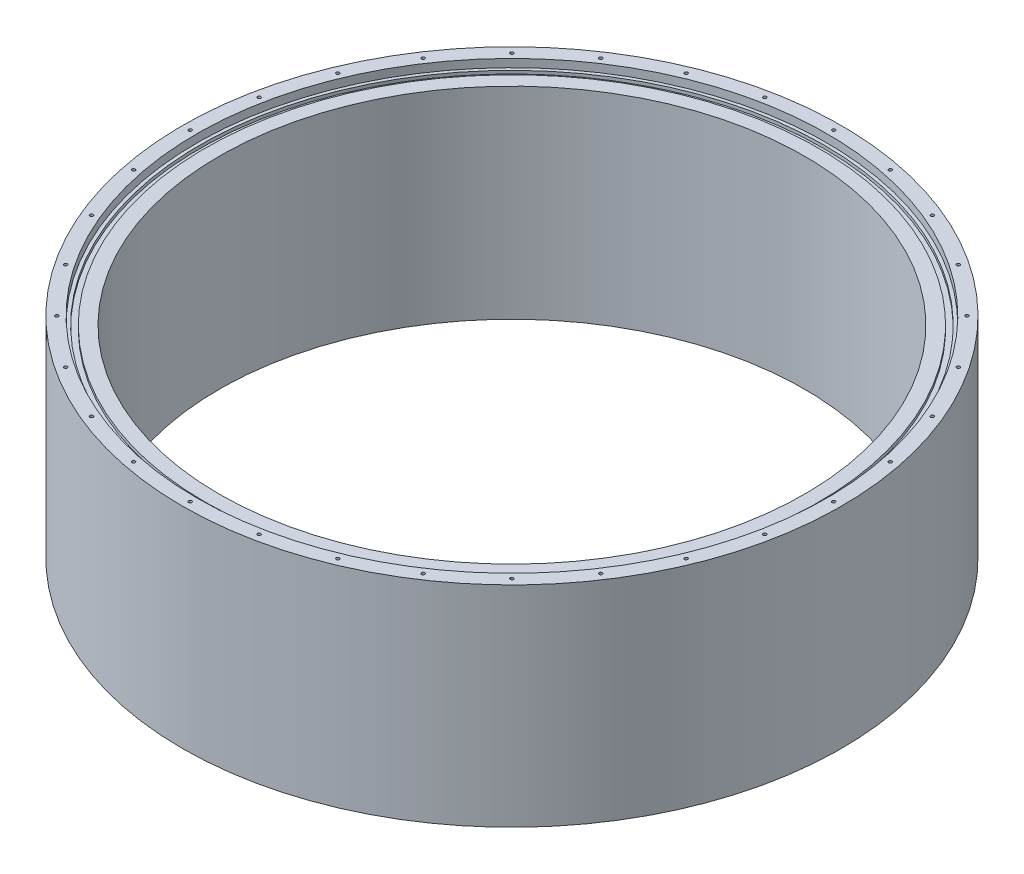
SolidWorks part; units mm, degrees
material "PVC Rigid"
ref_plane "Front" through (0, 0, 0) normal (0, 0, 1) x (1, 0, 0)
ref_plane "Top" through (0, 0, 0) normal (0, 1, 0) x (1, 0, 0)
ref_plane "Right" through (0, 0, 0) normal (1, 0, 0) x (0, 0, -1)
sketch "Sketch1" plane through (0, 0, 0) normal (0, 0, 1) x (1, 0, 0)
  line L0 (225.6, 74.685) -> (243, 74.685)
  line L1 (243, 74.685) -> (243, 80.885)
  line L2 (243, 80.885) -> (254, 80.885)
  line L3 (254, 80.885) -> (254, -80.885)
  line L4 (254, -80.885) -> (225.6, -80.885)
  line L5 (225.6, -80.885) -> (225.6, 74.685)
  line L6 (0, 80.885) -> (0, -80.885) construction
  line L7 (0, 0) -> (225.6, 0) construction
  dimension "D1" = 508
  dimension "D2" = 11
  dimension "D3" = 28.4
  dimension "D4" = 6.2
  dimension "D5" = 161.77
  dimension "D6" = 225.6
  dimension "D7" = 155.57
revolve "Revolve1" add sketch "Sketch1" angle 360 about L6
sketch "Sketch2" plane through (0, 0, 0) normal (0, 0, 1) x (1, 0, 0)
  line L0 (0, 80.885) -> (0, -80.885) construction
  line L1 (254, 80.885) -> (-254, 80.885) construction
  line L2 (-254, -80.885) -> (254, -80.885) construction
  line L3 (240.5, 72.272) -> (240.5, -77.587) construction
  line L4 (236.3344, 74.685) -> (240.5, 74.685)
  line L5 (236.3344, 74.685) -> (236.3344, 72.272)
  line L6 (236.3344, 72.272) -> (240.5, 72.272)
  line L7 (240.5, 74.685) -> (240.5, 72.272)
  line L8 (225.6, 74.685) -> (-225.6, 74.685) construction
  line L9 (225.6, 74.685) -> (-225.6, 74.685) construction
  line L10 (254, -80.885) -> (254, 80.885) construction
  line L12 (236.3344, -78.472) -> (240.5, -78.472) construction
  line L13 (236.3344, -78.472) -> (236.3344, -80.885) construction
  line L14 (236.3344, -80.885) -> (240.5, -80.885) construction
  line L15 (240.5, -78.472) -> (240.5, -80.885) construction
  dimension "D1" = 13.5
  dimension "D2" = 2.413
  dimension "D3" = 4.1656
revolve "Cut-Revolve1" cut sketch "Sketch2" angle 360 about L0
hole_wizard "M3x0.5 Tapped Hole1" positions "Sketch3" profile "Sketch4" tap size "M3x0.5" standard "ANSI Metric"
sketch "Sketch3" plane through (0, 80.885, 0) normal (0, 1, 0) x (1, 0, 0)
  point P0 (248, 0)
  dimension "D1" = 248
sketch "Sketch4" plane through (248, 80.885, 0) normal (1, 0, 0) x (0, 0, 1)
  line L0 (0, 0) -> (0, 10.2511)
  line L1 (0, 10.2511) -> (1.25, 9.5)
  line L2 (1.25, 9.5) -> (1.25, 0)
  line L5 (1.25, 0) -> (0, 0)
  line L10 (0, 10.2511) -> (-1.25, 9.5) construction
  line L11 (0, -6.35) -> (0, 107.95) construction
  dimension "Tap Drill Dia." = 2.5
  dimension "Tap Drill Depth" = 9.5
  dimension "Drill Angle" = 118
cosmetic thread "Hole Thread1" parameters "D1"=8, "D2"=3
pattern_circular "CirPattern1" count 32 over 360 about axis through (0, 0, 0) along (0, 1, 0) of "M3x0.5 Tapped Hole1"
mirror "Mirror1" about plane through (0, 0, 0) normal (0, 1, 0) of "CirPattern1", "M3x0.5 Tapped Hole1"
hole_wizard "Ø5.0mm Dowel Hole1" positions "Sketch5" profile "Sketch6" hole size "Ø5.0" standard "ANSI Metric"
sketch "Sketch5" plane through (0, -80.885, 0) normal (0, -1, 0) x (-1, 0, 0)
  line L2 (0, 0) -> (0, 204.5498) construction
  line L3 (-23.7697, 246.8583) -> (0, 0) construction
  line L4 (0, 0) -> (24.3723, -253.116) construction
  circle A0 centre (0, 0) radius 248 construction
  point P6 (-23.7697, 246.8583)
  point P8 (23.7697, -246.8583)
  dimension "D1" = 5.5
sketch "Sketch6" plane through (-23.7697, -80.885, 246.8583) normal (1, 0, 0) x (0, 0, -1)
  line L0 (0, 0) -> (0, 7.5172)
  line L1 (0, 7.5172) -> (2.525, 6)
  line L2 (2.525, 6) -> (2.525, 0)
  line L5 (2.525, 0) -> (0, 0)
  line L10 (0, 7.5172) -> (-2.525, 6) construction
  line L11 (0, -6.35) -> (0, 107.95) construction
  dimension "Hole Dia." = 5.05
  dimension "Hole Depth" = 6
  dimension "Drill Angle" = 118
